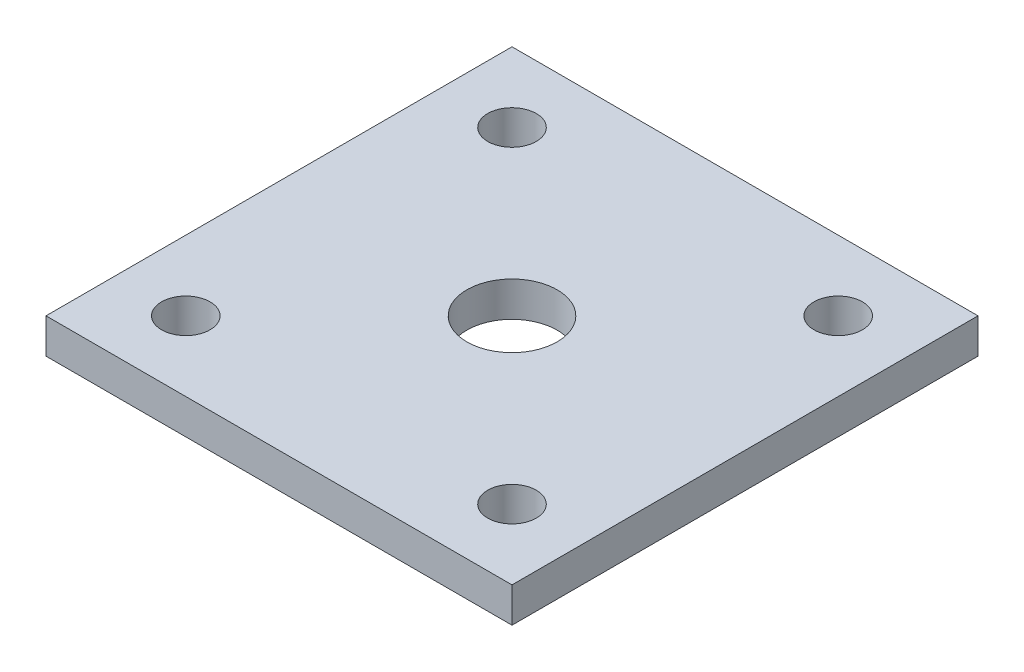
SolidWorks part; units mm, degrees
ref_plane "Front Plane" through (0, 0, 0) normal (0, 0, 1) x (1, 0, 0)
ref_plane "Top Plane" through (0, 0, 0) normal (0, 1, 0) x (1, 0, 0)
ref_plane "Right Plane" through (0, 0, 0) normal (1, 0, 0) x (0, 0, -1)
sketch "Sketch1" plane through (0, 0, 0) normal (0, 1, 0) x (1, 0, 0)
  line L1 (0, 0) -> (40, 0)
  line L2 (0, 0) -> (0, 40)
  line L3 (0, 40) -> (40, 40)
  line L4 (40, 0) -> (40, 40)
  circle A0 centre (20, 20) radius 3.875
  circle A1 centre (6, 34) radius 2.0828
  circle A2 centre (6, 6) radius 2.0828
  circle A3 centre (34, 6) radius 2.0828
  circle A4 centre (34, 34) radius 2.0828
  dimension "D3" = 6
  dimension "D5" = 6
  dimension "D7" = 6
  dimension "D9" = 6
  dimension "D1" = 40
  dimension "D2" = 40
  dimension "D4" = 6
  dimension "D6" = 6
  dimension "D8" = 6
  dimension "D10" = 6
extrude "Boss-Extrude1" add sketch "Sketch1" along normal blind 3
